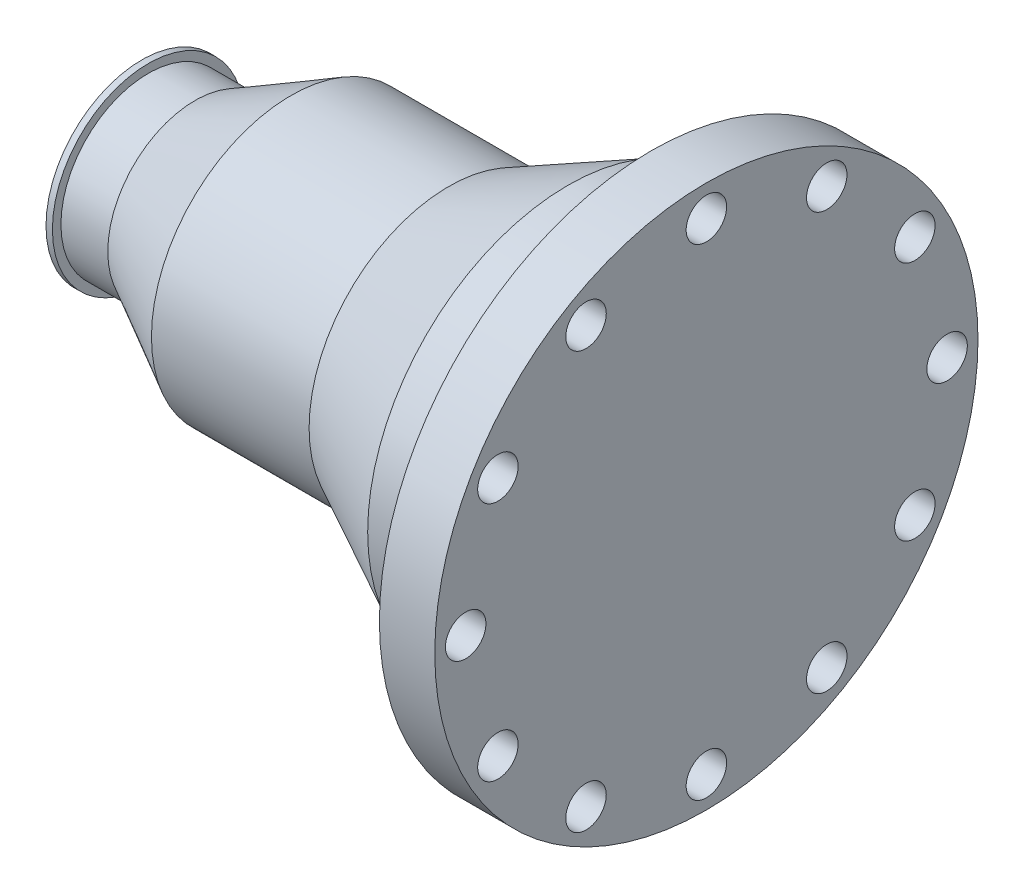
SolidWorks part; units mm, degrees
ref_plane "Спереди" through (0, 0, 0) normal (0, 0, 1) x (1, 0, 0)
ref_plane "Сверху" through (0, 0, 0) normal (0, 1, 0) x (1, 0, 0)
ref_plane "Справа" through (0, 0, 0) normal (1, 0, 0) x (0, 0, -1)
sketch "Эскиз1" plane through (0, 0, 0) normal (0, 0, 1) x (1, 0, 0)
  line L0 (0, 0) -> (265, 0)
  line L1 (0, 0) -> (0, 45)
  line L2 (0, 45) -> (3, 45)
  line L3 (3, 45) -> (3, 41)
  line L4 (3, 41) -> (25, 41)
  line L5 (25, 41) -> (70, 65.5)
  line L6 (70, 65.5) -> (144, 65.5)
  line L7 (144, 65.5) -> (200, 94)
  line L8 (200, 94) -> (220, 94)
  line L9 (220, 94) -> (220, 95)
  line L10 (220, 95) -> (239, 95)
  line L11 (239, 95) -> (239, 100)
  line L12 (239, 100) -> (239, 127.5)
  line L13 (239, 127.5) -> (265, 127.5)
  line L14 (265, 127.5) -> (265, 0)
revolve "Повернуть1" add sketch "Эскиз1" angle 360 about L0
sketch "Эскиз2" plane through (0, 0, 0) normal (0, 0, 1) x (1, 0, 0)
  line L0 (0, 0) -> (239, 0)
  line L1 (239, 95) -> (239, -95) construction
  line L2 (0, 0) -> (0, 31)
  line L3 (0, 45) -> (0, -45) construction
  line L4 (0, 31) -> (42, 31)
  line L5 (42, 31) -> (70, 38.5026)
  line L6 (70, 65.5) -> (70, -65.5) construction
  line L7 (90, 52.5) -> (142, 52.5)
  line L8 (143.5, 52.5) -> (146.6699, 52.5)
  line L9 (147.6699, 55) -> (200, 55)
  line L10 (200, 94) -> (200, -94) construction
  line L11 (200, 55) -> (208, 47)
  line L12 (210, 47) -> (239, 47)
  line L13 (239, 47) -> (239, 0)
  arc A0 (70, 38.5026) -> (90, 52.5) centre (107.8022, 5.7765) cw
  arc A1 (142, 52.5) -> (143.5, 52.5) centre (142.75, 49.8032) cw
  arc A2 (146.6699, 52.5) -> (147.6699, 55) centre (147.5934, 53.5806) cw
  arc A3 (208, 47) -> (210, 47) centre (209, 43.9727) cw
revolve "Вырез-Повернуть1" cut sketch "Эскиз2" angle 360 about L0
sketch "Эскиз3" plane through (0, 0, 0) normal (1, 0, 0) x (0, 0, -1)
  circle A0 centre (0, 113) radius 9.5
extrude "Вырез-Вытянуть1" cut sketch "Эскиз3" along normal through all
sketch "Эскиз4" plane through (0, 0, 0) normal (1, 0, 0) x (0, 0, -1)
  circle A0 centre (-56.5, 97.8609) radius 9.5
extrude "Вырез-Вытянуть2" cut sketch "Эскиз4" along normal through all
sketch "Эскиз5" plane through (0, 0, 0) normal (1, 0, 0) x (0, 0, -1)
  circle A0 centre (-97.8609, 56.5) radius 9.5
extrude "Вырез-Вытянуть3" cut sketch "Эскиз5" along normal through all
sketch "Эскиз6" plane through (0, 0, 0) normal (1, 0, 0) x (0, 0, -1)
  circle A0 centre (-113, 0) radius 9.5
extrude "Вырез-Вытянуть4" cut sketch "Эскиз6" along normal through all
sketch "Эскиз7" plane through (0, 0, 0) normal (1, 0, 0) x (0, 0, -1)
  circle A0 centre (-97.8609, -56.5) radius 9.5
extrude "Вырез-Вытянуть5" cut sketch "Эскиз7" along normal through all
sketch "Эскиз8" plane through (0, 0, 0) normal (1, 0, 0) x (0, 0, -1)
  circle A0 centre (-56.5, -97.8609) radius 9.5
extrude "Вырез-Вытянуть6" cut sketch "Эскиз8" along normal through all
sketch "Эскиз9" plane through (0, 0, 0) normal (1, 0, 0) x (0, 0, -1)
  circle A0 centre (0, -113) radius 9.5
extrude "Вырез-Вытянуть7" cut sketch "Эскиз9" along normal through all
sketch "Эскиз10" plane through (0, 0, 0) normal (1, 0, 0) x (0, 0, -1)
  circle A0 centre (56.5, -97.8609) radius 9.5
extrude "Вырез-Вытянуть8" cut sketch "Эскиз10" along normal through all
sketch "Эскиз11" plane through (0, 0, 0) normal (1, 0, 0) x (0, 0, -1)
  circle A0 centre (97.8609, -56.5) radius 9.5
extrude "Вырез-Вытянуть9" cut sketch "Эскиз11" along normal through all
sketch "Эскиз12" plane through (0, 0, 0) normal (1, 0, 0) x (0, 0, -1)
  circle A0 centre (113, 0) radius 9.5
extrude "Вырез-Вытянуть10" cut sketch "Эскиз12" along normal through all
sketch "Эскиз13" plane through (0, 0, 0) normal (1, 0, 0) x (0, 0, -1)
  circle A0 centre (97.8609, 56.5) radius 9.5
extrude "Вырез-Вытянуть11" cut sketch "Эскиз13" along normal through all
sketch "Эскиз14" plane through (0, 0, 0) normal (1, 0, 0) x (0, 0, -1)
  circle A0 centre (56.5, 97.8609) radius 9.5
extrude "Вырез-Вытянуть12" cut sketch "Эскиз14" along normal through all
